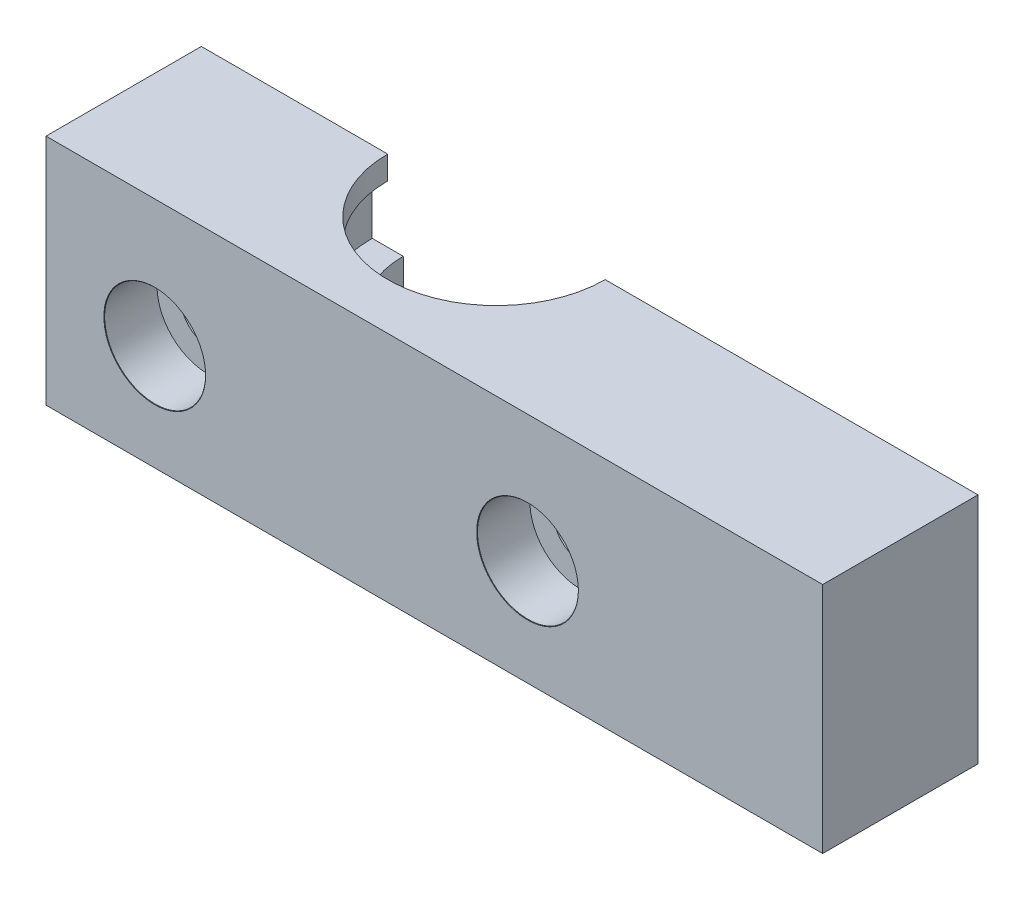
SolidWorks part; units mm, degrees
ref_plane "Front Plane" through (0, 0, 0) normal (0, 0, 1) x (1, 0, 0)
ref_plane "Top Plane" through (0, 0, 0) normal (0, 1, 0) x (1, 0, 0)
ref_plane "Right Plane" through (0, 0, 0) normal (1, 0, 0) x (0, 0, -1)
sketch "Sketch1" plane through (0, 0, 0) normal (0, 0, 1) x (1, 0, 0)
  line L1 (-19, 2) -> (31, 2)
  line L2 (-19, 2) -> (-19, 17)
  line L3 (-19, 17) -> (31, 17)
  line L4 (31, 2) -> (31, 17)
  dimension "D1" = 15
  dimension "D2" = 50
  dimension "D3" = 19
  dimension "D4" = 17
extrude "Boss-Extrude1" add sketch "Sketch1" along normal blind 10
sketch "Sketch2" plane through (0, 0, 0) normal (1, 0, 0) x (0, 0, -1)
  line L0 (0, 2) -> (0, 17) construction
  line L1 (0, 17) -> (-7, 17)
  line L2 (-10, 17) -> (0, 17) construction
  line L3 (-7, 17) -> (-7, 15.5)
  line L4 (-7, 15.5) -> (-8, 15.5)
  line L5 (-8, 15.5) -> (-8, 11.8)
  line L6 (-8, 11.8) -> (-6, 11.8)
  line L7 (-6, 11.8) -> (-6, 5.8)
  line L8 (-6, 5.8) -> (-8, 5.8)
  line L9 (-8, 5.8) -> (-8, 2.8)
  line L10 (-8, 2.8) -> (-6.25, 2.8)
  line L16 (0, 17) -> (0, 2)
  line L17 (-6.25, 2.8) -> (-6.25, 2)
  line L19 (0, 2) -> (-6.25, 2)
  dimension "D1" = 7
  dimension "D2" = 1.5
  dimension "D3" = 1
  dimension "D4" = 3.7
  dimension "D5" = 6
  dimension "D6" = 6
  dimension "D7" = 8
  dimension "D8" = 3
  dimension "D9" = 6.25
  dimension "D11" = 15
revolve "Cut-Revolve1" cut sketch "Sketch2" angle 360 about L0
sketch "Sketch3" plane through (0, 0, 10) normal (0, 0, 1) x (1, 0, 0)
  line L0 (-6, 8.8) -> (-12, 8.8) construction
  line L1 (-6, 11.8) -> (-6, 5.8) construction
  line L2 (-12, 8.8) -> (12, 8.8) construction
  dimension "D1" = 6
  dimension "D2" = 24
hole_wizard "CBORE for M3 Hex Socket Head Cap Screw1" positions "3DSketch2" profile "Sketch4" counterbore size "M3" standard "DIN" end condition through all
sketch3d "3DSketch2"
  point P0 (-12, 8.8, 10)
  point P3 (12, 8.8, 10)
sketch "Sketch4" plane through (-12, 8.8, 10) normal (1, 0, 0) x (0, -1, 0)
  line L0 (0, 0) -> (0, 10)
  line L1 (0, 10) -> (1.7, 10)
  line L3 (1.7, 10) -> (1.7, 3.4)
  line L4 (3.25, 3.4) -> (1.7, 3.4)
  line L5 (3.25, 3.4) -> (3.25, 0.025)
  line L6 (3.25, 0.025) -> (3.275, 0)
  line L7 (3.275, 0) -> (0, 0)
  line L8 (-3.25, 0.025) -> (-3.275, 0) construction
  line L11 (0, -6.35) -> (0, 107.95) construction
  dimension "Thru Hole Dia." = 3.4
  dimension "Thru Hole Depth" = 10
  dimension "C'Bore Dia." = 6.5
  dimension "C'Bore Depth" = 3.4
  dimension "Near C'Sink Dia." = 6.55
  dimension "Near C'Sink Angle" = 90
